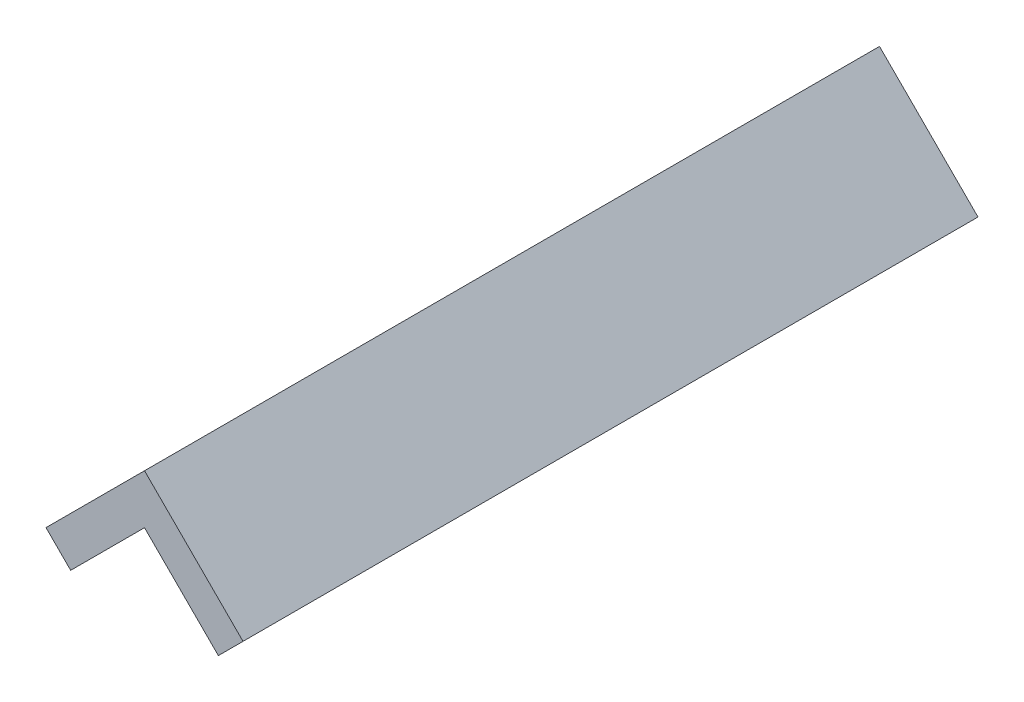
SolidWorks part; units mm, degrees
ref_plane "Plano frontal" through (0, 0, 0) normal (0, 0, 1) x (1, 0, 0)
ref_plane "Plano superior" through (0, 0, 0) normal (0, 1, 0) x (1, 0, 0)
ref_plane "Plano direito" through (0, 0, 0) normal (1, 0, 0) x (0, 0, -1)
sketch "Esboço1" plane through (0, 0, 0) normal (0, 0, 1) x (1, 0, 0)
  line L0 (8.9803, 8.9803) -> (17.9605, 0)
  line L1 (0, 0) -> (2.2486, -2.2486)
  line L2 (8.9803, -1.1797) -> (8.9803, 8.9803) construction
  line L3 (2.2486, -2.2486) -> (8.9803, 4.4831)
  line L4 (17.9605, 0) -> (15.7119, -2.2486)
  line L5 (8.9803, 8.9803) -> (0, 0)
  line L6 (15.7119, -2.2486) -> (8.9803, 4.4831)
  dimension "D1" = 90
  dimension "D2" = 12.7
  dimension "D3" = 3.18
extrude "Ressalto-extrusão1" add sketch "Esboço1" along normal blind 67 contours L0 L4 L6 L3 L1 L5
